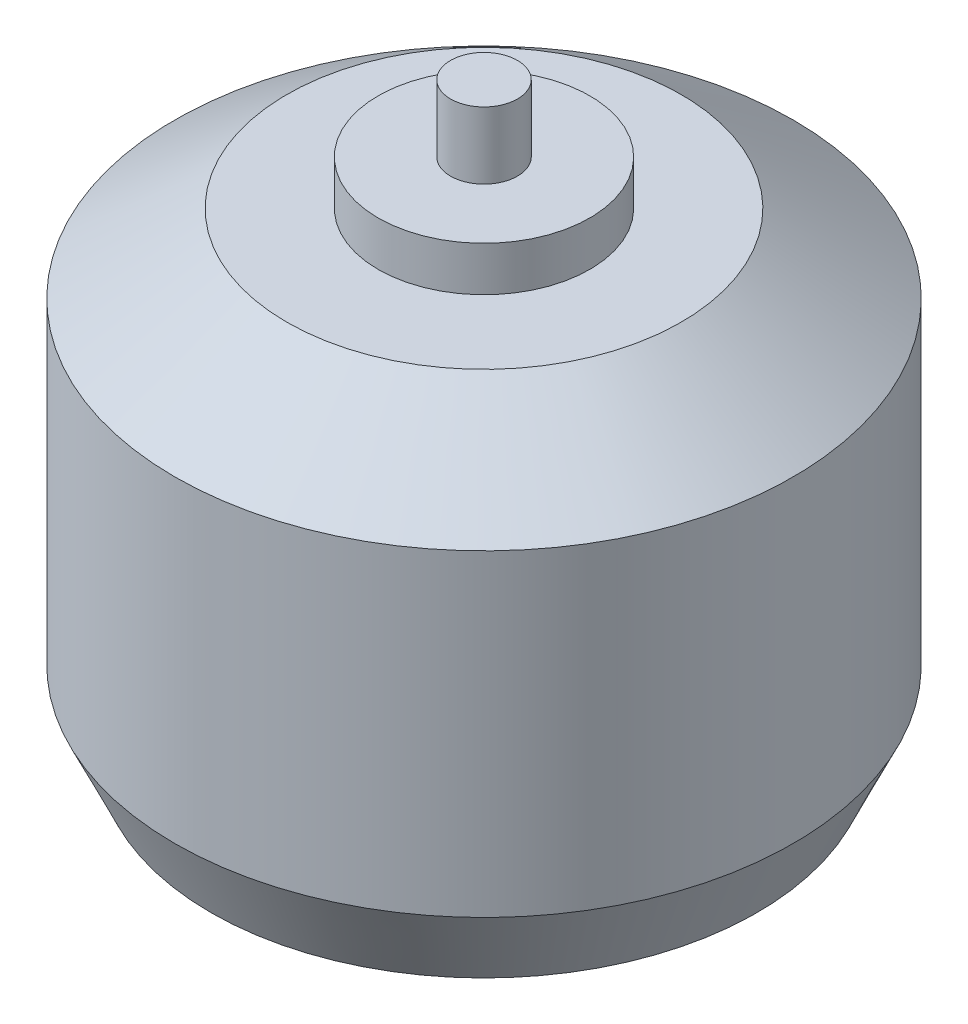
SolidWorks part; units mm, degrees
ref_plane "Front Plane" through (0, 0, 0) normal (0, 0, 1) x (1, 0, 0)
ref_plane "Top Plane" through (0, 0, 0) normal (0, 1, 0) x (1, 0, 0)
ref_plane "Right Plane" through (0, 0, 0) normal (1, 0, 0) x (0, 0, -1)
sketch "Sketch1" plane through (0, 0, 0) normal (1, 0, 0) x (0, 0, -1)
  line L0 (0, 0) -> (-12.25, 0)
  line L1 (-12.25, 0) -> (-13.875, 3.5)
  line L2 (-13.875, 3.5) -> (-13.875, 17.75)
  line L3 (-13.875, 17.75) -> (-8.85, 21.25)
  line L4 (-8.85, 21.25) -> (-4.75, 21.25)
  line L5 (-4.75, 21.25) -> (-4.75, 23.25)
  line L6 (-4.75, 23.25) -> (-1.5, 23.25)
  line L7 (-1.5, 23.25) -> (-1.5, 26.25)
  line L8 (-1.5, 26.25) -> (0, 26.25)
  line L9 (0, 26.25) -> (0, 0)
  dimension "D1" = 13.875
  dimension "D2" = 23.25
  dimension "D3" = 1.5
  dimension "D4" = 3
  dimension "D5" = 4.75
  dimension "D6" = 2
  dimension "D7" = 8.85
  dimension "D8" = 3.5
  dimension "D9" = 3.5
  dimension "D10" = 12.25
revolve "Revolve1" add sketch "Sketch1" angle 360 about L9
